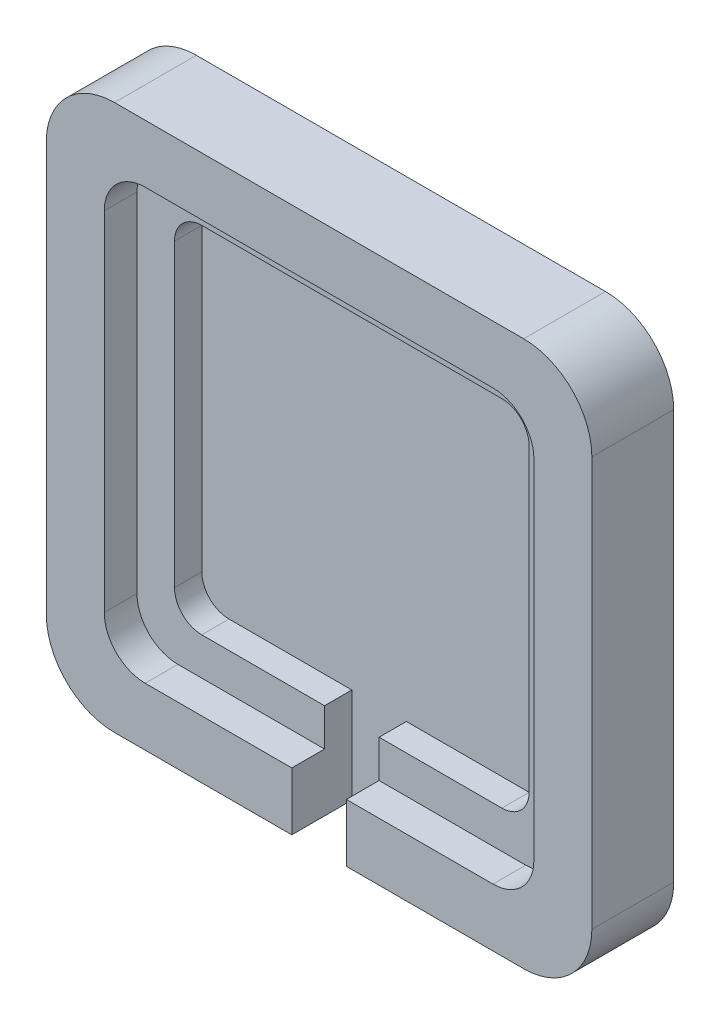
SolidWorks part; units mm, degrees
ref_plane "Ebene vorne" through (0, 0, 0) normal (0, 0, 1) x (1, 0, 0)
ref_plane "Ebene oben" through (0, 0, 0) normal (0, 1, 0) x (1, 0, 0)
ref_plane "Ebene rechts" through (0, 0, 0) normal (1, 0, 0) x (0, 0, -1)
sketch "Skizze1" plane through (0, 0, 0) normal (0, 0, 1) x (1, 0, 0)
  line L1 (20, -20) -> (-20, -20)
  line L2 (20, -20) -> (20, 20)
  line L3 (20, 20) -> (-20, 20)
  line L4 (-20, -20) -> (-20, 20)
  line L5 (20, -20) -> (-20, 20) construction
  line L6 (20, 20) -> (-20, -20) construction
  point P0 (0, 0)
  dimension "D1" = 40
  dimension "D2" = 40
extrude "Aufsatz-Linear austragen1" add sketch "Skizze1" along normal blind 6
fillet "Verrundung1" radius 5 4 edges at (-20, -20, 3) (-20, 20, 3) (20, 20, 3) (20, -20, 3)
sketch "Skizze2" plane through (0, 0, 6) normal (0, 0, 1) x (1, 0, 0)
  line L1 (15.75, -15.75) -> (-15.75, -15.75)
  line L2 (15.75, -15.75) -> (15.75, 15.75)
  line L3 (15.75, 15.75) -> (-15.75, 15.75)
  line L4 (-15.75, -15.75) -> (-15.75, 15.75)
  line L5 (15.75, -15.75) -> (-15.75, 15.75) construction
  line L6 (15.75, 15.75) -> (-15.75, -15.75) construction
  point P0 (0, 0)
  dimension "D1" = 31.5
  dimension "D2" = 31.5
extrude "Schnitt-Linear austragen1" cut sketch "Skizze2" against normal blind 2.4
fillet "Verrundung2" radius 3 4 edges at (15.75, 15.75, 4.8) (15.75, -15.75, 4.8) (-15.75, -15.75, 4.8) (-15.75, 15.75, 4.8)
sketch "Skizze3" plane through (0, 0, 3.6) normal (0, 0, 1) x (1, 0, 0)
  line L1 (-13, -13) -> (13, -13)
  line L2 (-13, -13) -> (-13, 13)
  line L3 (-13, 13) -> (13, 13)
  line L4 (13, -13) -> (13, 13)
  line L5 (-13, -13) -> (13, 13) construction
  line L6 (-13, 13) -> (13, -13) construction
  point P0 (0, 0)
  dimension "D1" = 26
  dimension "D2" = 26
extrude "Schnitt-Linear austragen2" cut sketch "Skizze3" against normal blind 2
fillet "Verrundung3" radius 2 4 edges at (13, -13, 2.6) (-13, -13, 2.6) (-13, 13, 2.6) (13, 13, 2.6)
sketch "Skizze4" plane through (0, 0, 6) normal (0, 0, 1) x (1, 0, 0)
  line L0 (0, 0) -> (0, -17.2969) construction
  line L1 (2, -12.2775) -> (-2, -12.2775)
  line L2 (2, -12.2775) -> (2, -22.3164)
  line L3 (2, -22.3164) -> (-2, -22.3164)
  line L4 (-2, -12.2775) -> (-2, -22.3164)
  line L5 (2, -12.2775) -> (-2, -22.3164) construction
  line L6 (2, -22.3164) -> (-2, -12.2775) construction
  point P0 (0, -17.2969)
  dimension "D1" = 4
extrude "Schnitt-Linear austragen3" cut sketch "Skizze4" against normal up to surface (4.4 mm away) up to face at (0, 0, 1.6)
